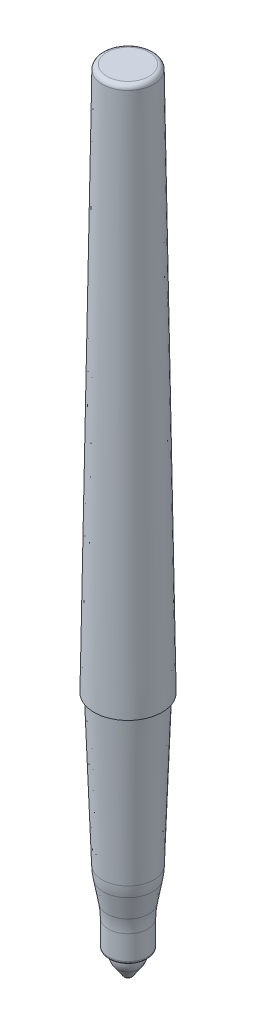
SolidWorks part; units mm, degrees
ref_plane "Front Plane" through (0, 0, 0) normal (0, 0, 1) x (1, 0, 0)
ref_plane "Top Plane" through (0, 0, 0) normal (0, 1, 0) x (1, 0, 0)
ref_plane "Right Plane" through (0, 0, 0) normal (1, 0, 0) x (0, 0, -1)
sketch "Sketch1" plane through (0, 0, 0) normal (0, 0, 1) x (1, 0, 0)
  line L0 (0.508, 0) -> (2.286, 2.54)
  line L1 (0, 0) -> (5.588, 0)
  line L2 (0, 0) -> (0, 129.54)
  line L3 (0, 129.54) -> (5.588, 129.54)
  line L4 (5.588, 0) -> (5.588, 129.54)
  line L5 (2.286, 2.54) -> (2.286, 3.81)
  line L6 (2.286, 3.81) -> (3.2131, 3.81)
  line L7 (3.2131, 3.81) -> (3.2131, 9.398)
  line L8 (4.193, 14.859) -> (5.08, 40.259)
  line L9 (5.08, 40.259) -> (5.588, 40.259)
  line L10 (3.2131, 9.398) -> (4.193, 14.859)
  line L11 (0, 0) -> (0, 256.4951) construction
  line L13 (4.191, 129.54) -> (5.588, 40.259)
  dimension "D1" = 5.588
  dimension "D2" = 0.9271
  dimension "D3" = 0.508
  dimension "D4" = 25.4
  dimension "D5" = 2.54
  dimension "D6" = 3.81
  dimension "D7" = 9.398
  dimension "D8" = 2.286
  dimension "D9" = 0.508
  dimension "D10" = 5.461
  dimension "D11" = 2
  dimension "D12" = 129.54
  dimension "D13" = 4.191
revolve "Revolve1" add sketch "Sketch1" angle 360 about L11
fillet "Fillet1" radius 0.508 1 edges at (0, 0, -0.508)
fillet "Fillet2" radius 2.54 1 edges at (0, 2.54, -2.286)
fillet "Fillet3" radius 12.7 2 edges at (0, 14.859, -4.193) (0, 9.398, -3.2131)
fillet "Fillet4" radius 0.508 1 edges at (0, 3.81, -3.2131)
fillet "Fillet5" radius 0.762 1 edges at (0, 129.54, -4.191)
